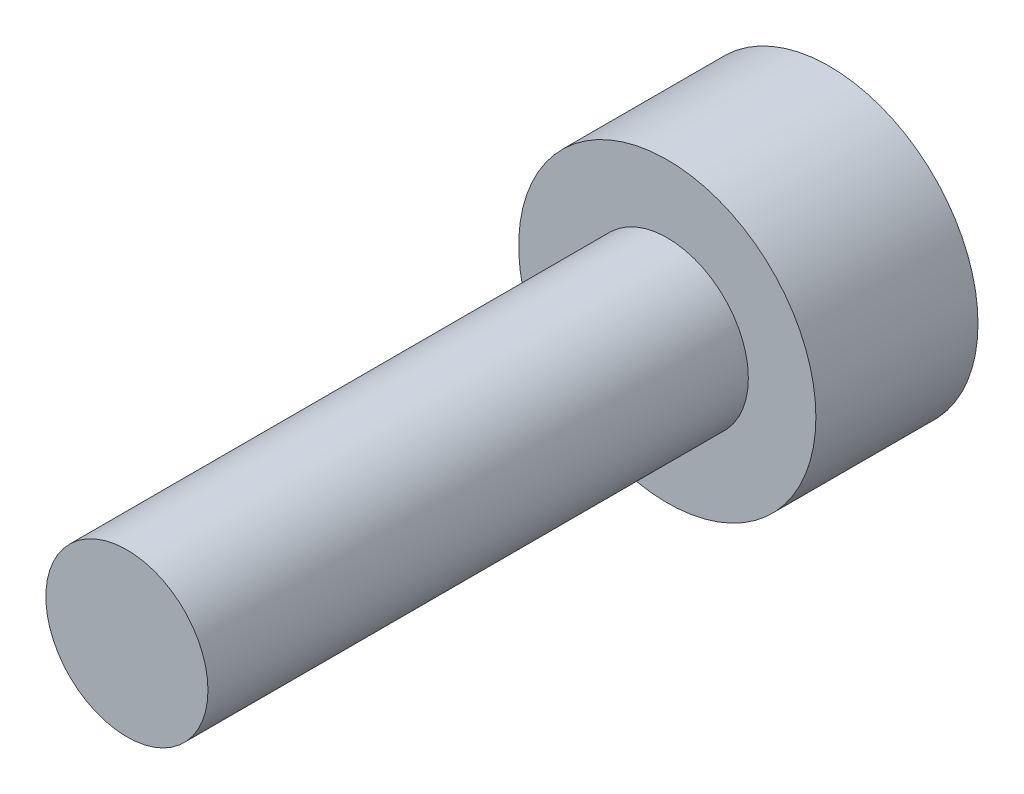
SolidWorks part; units mm, degrees
material "不锈钢 (铁素体)"
ref_plane "前视基准面" through (0, 0, 0) normal (0, 0, 1) x (1, 0, 0)
ref_plane "上视基准面" through (0, 0, 0) normal (0, 1, 0) x (1, 0, 0)
ref_plane "右视基准面" through (0, 0, 0) normal (1, 0, 0) x (0, 0, -1)
other "Configuration Table"
sketch "草图1" plane through (0, 0, 0) normal (0, 0, 1) x (1, 0, 0)
  circle A0 centre (0, 0) radius 2.75
  dimension "D1" = 5.5
extrude "凸台-拉伸1" add sketch "草图1" along normal blind 3
sketch "草图2" plane through (0, 0, 3) normal (0, 0, 1) x (1, 0, 0)
  circle A0 centre (0, 0) radius 1.5
  dimension "D1" = 3
extrude "凸台-拉伸2" add sketch "草图2" along normal blind 10
